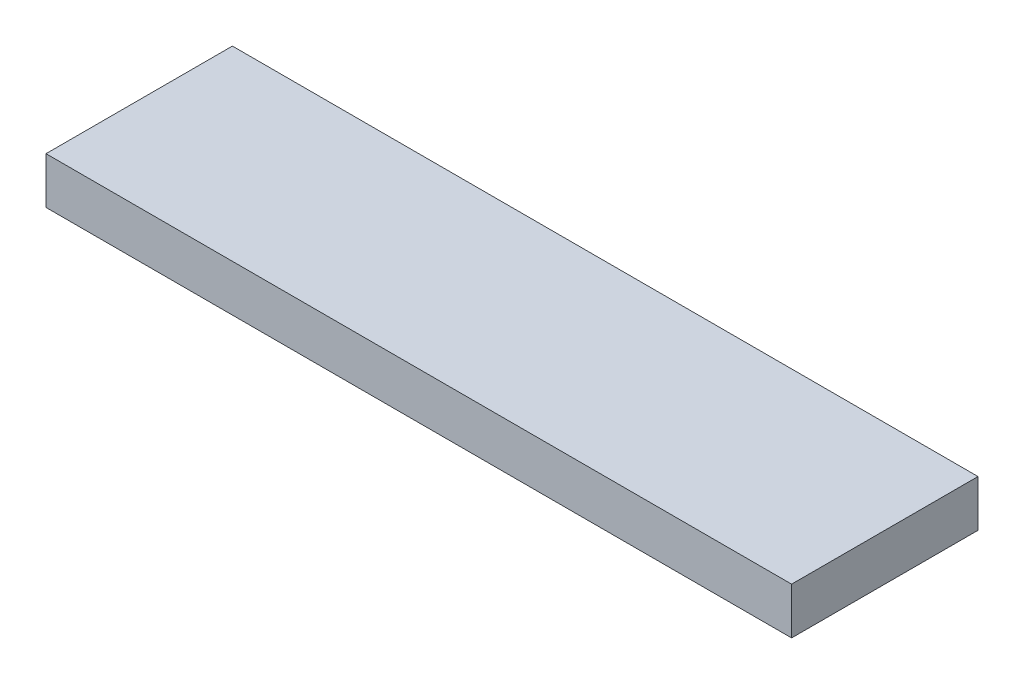
SolidWorks part; units mm, degrees
ref_plane "Front Plane" through (0, 0, 0) normal (0, 0, 1) x (1, 0, 0)
ref_plane "Top Plane" through (0, 0, 0) normal (0, 1, 0) x (1, 0, 0)
ref_plane "Right Plane" through (0, 0, 0) normal (1, 0, 0) x (0, 0, -1)
sketch "Sketch1" plane through (0, 0, 0) normal (0, 1, 0) x (1, 0, 0)
  line L1 (-101.6, -25.4) -> (101.6, -25.4)
  line L2 (-101.6, -25.4) -> (-101.6, 25.4)
  line L3 (-101.6, 25.4) -> (101.6, 25.4)
  line L4 (101.6, -25.4) -> (101.6, 25.4)
  line L5 (-101.6, -25.4) -> (101.6, 25.4) construction
  line L6 (-101.6, 25.4) -> (101.6, -25.4) construction
  point P0 (0, 0)
  dimension "D1" = 203.2
  dimension "D2" = 50.8
extrude "Boss-Extrude1" add sketch "Sketch1" along normal blind 12.7
